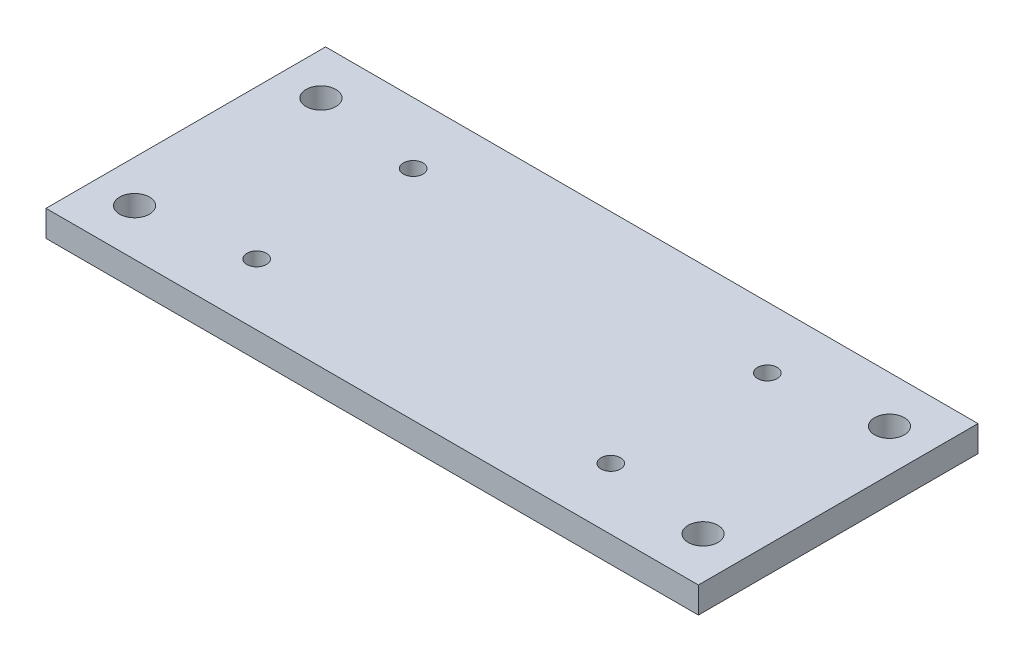
SolidWorks part; units mm, degrees
material "Alloy Steel"
ref_plane "Front Plane" through (0, 0, 0) normal (0, 0, 1) x (1, 0, 0)
ref_plane "Top Plane" through (0, 0, 0) normal (0, 1, 0) x (1, 0, 0)
ref_plane "Right Plane" through (0, 0, 0) normal (1, 0, 0) x (0, 0, -1)
sketch "Sketch1" plane through (0, 0, 0) normal (0, 1, 0) x (1, 0, 0)
  line L1 (0, 0) -> (175, 0)
  line L2 (0, 0) -> (0, 75)
  line L3 (0, 75) -> (175, 75)
  line L4 (175, 0) -> (175, 75)
  dimension "D1" = 175
  dimension "D2" = 75
extrude "Boss-Extrude1" add sketch "Sketch1" along normal blind 7
sketch "Sketch3" plane through (0, 0, 0) normal (0, 0, 1) x (1, 0, 0)
  line L0 (87.5, 7) -> (87.5, 61)
  line L1 (0, 7) -> (175, 7) construction
  dimension "D1" = 54
ref_plane "Plane1" through (87.5, 0, 0) normal (1, 0, 0) x (0, 0, -1)
sketch "Sketch4" plane through (87.5, 0, 0) normal (1, 0, 0) x (0, 0, -1)
  line L0 (0, 61) -> (88, 61)
  line L1 (0, 7) -> (0, 61) construction
  line L3 (58.5, 2.1469) -> (58.5, 52.7221)
  line L4 (75, 7) -> (75, 0) construction
  dimension "D1" = 16.5
  dimension "D2" = 29.5
sketch "Sketch5" plane through (0, 0, 0) normal (0, -1, 0) x (1, 0, 0)
  line L0 (10, 0) -> (10, -5)
  line L1 (0, 0) -> (175, 0) construction
  line L2 (10, -5) -> (5, -5)
  line L3 (5, -5) -> (5, -10)
  line L4 (5, -10) -> (0, -10)
  line L5 (0, -75) -> (0, 0) construction
  line L6 (0, -10) -> (0, 0)
  line L7 (0, 0) -> (10, 0)
  line L8 (87.5, -2.75) -> (87.5, 2.75) construction
  line L9 (175, 0) -> (165, 0)
  line L10 (175, -10) -> (175, 0)
  line L11 (170, -10) -> (175, -10)
  line L12 (170, -5) -> (170, -10)
  line L13 (165, -5) -> (170, -5)
  line L14 (165, 0) -> (165, -5)
  line L15 (0, -37.5) -> (175, -37.5) construction
  line L16 (175, 0) -> (175, -75) construction
  line L17 (165, -75) -> (165, -70)
  line L18 (165, -70) -> (170, -70)
  line L19 (170, -70) -> (170, -65)
  line L20 (170, -65) -> (175, -65)
  line L21 (175, -65) -> (175, -75)
  line L22 (175, -75) -> (165, -75)
  line L23 (0, -75) -> (10, -75)
  line L24 (0, -65) -> (0, -75)
  line L25 (5, -65) -> (0, -65)
  line L26 (5, -70) -> (5, -65)
  line L27 (10, -70) -> (5, -70)
  line L28 (10, -75) -> (10, -70)
  dimension "D1" = 10
  dimension "D2" = 10
  dimension "D3" = 5
  dimension "D4" = 5
sketch "Sketch6" plane through (0, 0, 0) normal (0, -1, 0) x (1, 0, 0)
  line L1 (0, 0) -> (175, 0)
  line L2 (0, 0) -> (0, -75)
  line L3 (0, -75) -> (175, -75)
  line L4 (175, 0) -> (175, -75)
sketch "Sketch2" plane through (0, 7, 0) normal (0, 1, 0) x (1, 0, 0)
  line L0 (87.5, 0) -> (87.5, 75) construction
  line L1 (0, 0) -> (175, 0) construction
  line L2 (175, 75) -> (0, 75) construction
  line L3 (0, 37.5) -> (11.25, 37.5) construction
  line L4 (0, 75) -> (0, 0) construction
  line L5 (11.25, 62.5) -> (11.25, 12.5) construction
  line L6 (163.75, 62.5) -> (163.75, 12.5) construction
  line L7 (175, 37.5) -> (163.75, 37.5) construction
  line L8 (0, 37.5) -> (40, 37.5) construction
  line L9 (40, 58.5) -> (40, 16.5) construction
  line L10 (175, 37.5) -> (135, 37.5) construction
  line L11 (135, 58.5) -> (135, 16.5) construction
  circle A0 centre (11.25, 62.5) radius 4
  circle A1 centre (11.25, 12.5) radius 4
  circle A2 centre (163.75, 12.5) radius 4
  circle A3 centre (163.75, 62.5) radius 4
  circle A4 centre (40, 58.5) radius 2.625
  circle A5 centre (40, 16.5) radius 2.625
  circle A6 centre (135, 16.5) radius 2.625
  circle A7 centre (135, 58.5) radius 2.625
  dimension "D1" = 8
  dimension "D4" = 5.25
  dimension "D2" = 50
  dimension "D3" = 152.5
  dimension "D5" = 42
  dimension "D6" = 95
extrude "Cut-Extrude1" cut sketch "Sketch2" against normal through all
